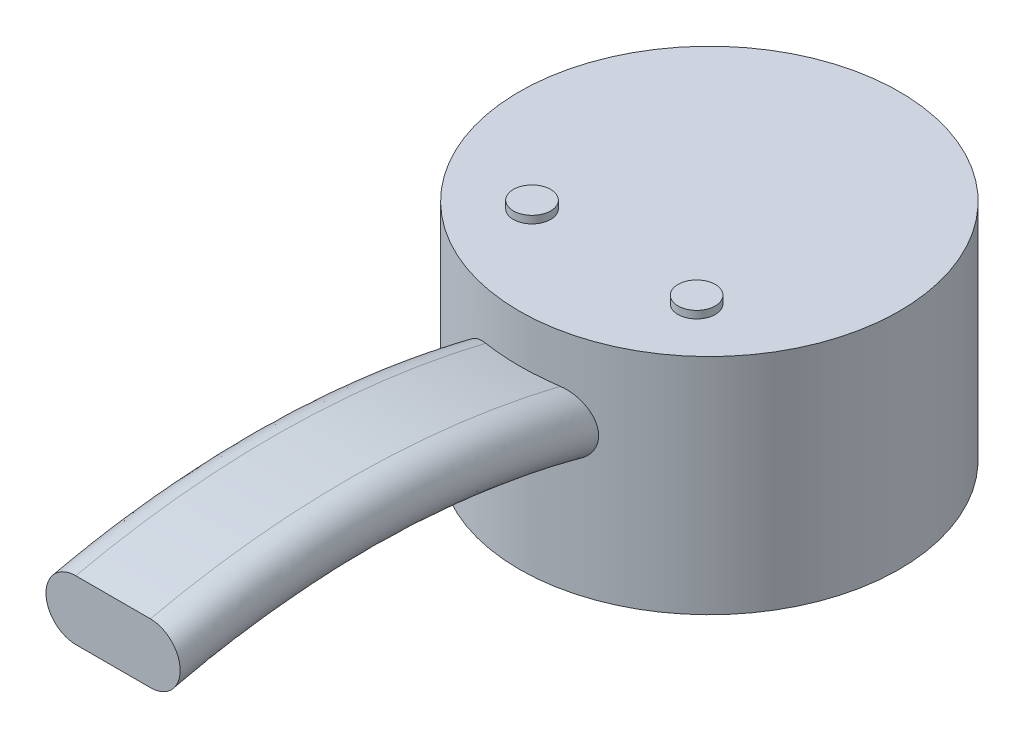
SolidWorks part; units mm, degrees
ref_plane "Front Plane" through (0, 0, 0) normal (0, 0, 1) x (1, 0, 0)
ref_plane "Top Plane" through (0, 0, 0) normal (0, 1, 0) x (1, 0, 0)
ref_plane "Right Plane" through (0, 0, 0) normal (1, 0, 0) x (0, 0, -1)
sketch "Sketch1" plane through (0, 0, 0) normal (0, 1, 0) x (1, 0, 0)
  circle A0 centre (0, 0) radius 25.5
  dimension "D1" = 51
extrude "Boss-Extrude1" add sketch "Sketch1" along normal blind 30
shell "Shell1" thickness 10
sketch "Sketch3" plane through (0, 0, 0) normal (0, 0, 1) x (1, 0, 0)
  line L0 (0, 0) -> (0, 10)
  line L1 (5, 10) -> (-5, 10) construction
  line L2 (5, 6) -> (-5, 6)
  line L3 (5, 14) -> (-5, 14)
  arc A0 (5, 6) -> (5, 14) centre (5, 10) ccw
  arc A1 (-5, 14) -> (-5, 6) centre (-5, 10) ccw
  point P5 (0, 10)
  point P10 (0, 0)
  point P11 (0, 0)
  dimension "D3" = 4
  dimension "D1" = 10
  dimension "D2" = 10
ref_plane "Plane1" through (0, 0, 80) normal (0, 0, 1) x (1, 0, 0)
sketch "Sketch4" plane through (0, 0, 80) normal (0, 0, 1) x (1, 0, 0)
  line L0 (5, 20) -> (-5, 20) construction
  line L1 (0, 4.606) -> (0, 33.7274) construction
  line L4 (5, 16) -> (-5, 16)
  line L5 (5, 24) -> (-5, 24)
  arc A2 (5, 16) -> (5, 24) centre (5, 20) ccw
  arc A3 (-5, 24) -> (-5, 16) centre (-5, 20) ccw
  point P1 (0, 0)
  point P10 (0, 20)
  dimension "D1" = 10
sketch "Sketch5" plane through (0, 0, 0) normal (1, 0, 0) x (0, 0, -1)
  arc A0 (0, 10) -> (-80, 20) centre (-53.5298, -93.2382) ccw
  point P3 (-40.9285, 27.3561)
sweep "Sweep1" add profiles "Sketch4" path "Sketch5"
sketch "Sketch6" plane through (0, 30, 0) normal (0, 1, 0) x (1, 0, 0)
  line L0 (0, 0) -> (0, -25.5) construction
  line L1 (0, -12.75) -> (-22.0836, -12.75) construction
  circle A0 centre (0, 0) radius 25.5 construction
  circle A1 centre (-11.0418, -12.75) radius 2.5
  circle A2 centre (11.0418, -12.75) radius 2.5
  dimension "D1" = 5
extrude "Boss-Extrude2" add sketch "Sketch6" along normal blind 1
